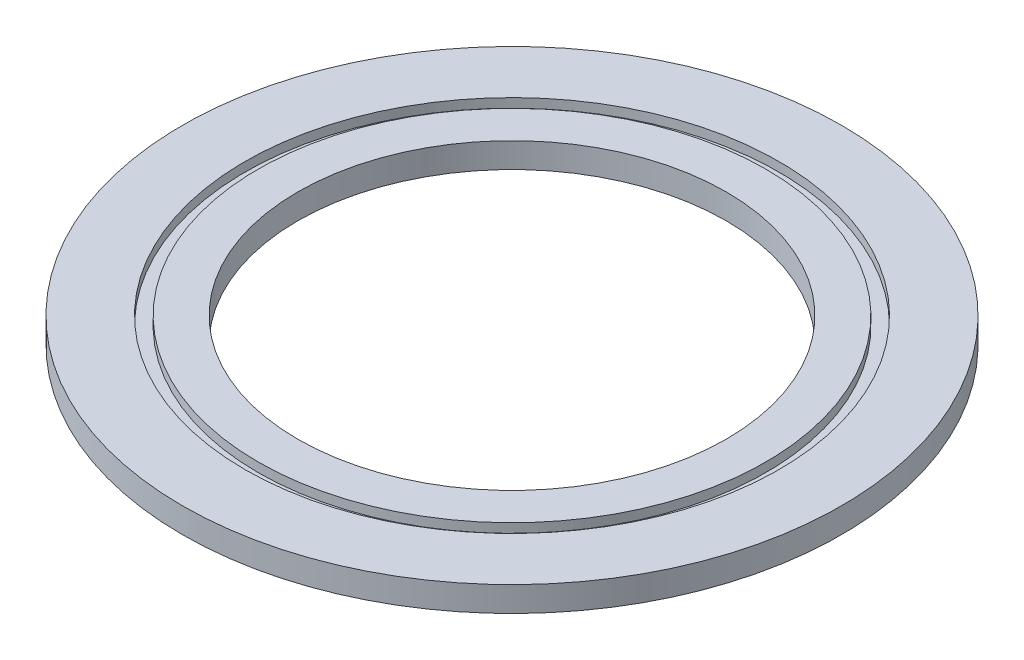
SolidWorks part; units mm, degrees
material "Pine"
ref_plane "Front Plane" through (0, 0, 0) normal (0, 0, 1) x (1, 0, 0)
ref_plane "Top Plane" through (0, 0, 0) normal (0, 1, 0) x (1, 0, 0)
ref_plane "Right Plane" through (0, 0, 0) normal (1, 0, 0) x (0, 0, -1)
sketch "Sketch1" plane through (0, 0, 0) normal (0, 1, 0) x (1, 0, 0)
  circle A0 centre (0, 0) radius 250
  circle A2 centre (0, 0) radius 162.5
  dimension "D1" = 500
  dimension "D2" = 325
extrude "Boss-Extrude1" add sketch "Sketch1" along normal mid plane 19
sketch "Sketch2" plane through (0, 9.5, 0) normal (0, 1, 0) x (1, 0, 0)
  circle A0 centre (0, 0) radius 202.5
  circle A1 centre (0, 0) radius 192.5
  dimension "D1" = 405
  dimension "D2" = 10
extrude "Cut-Extrude1" cut sketch "Sketch2" against normal blind 7
